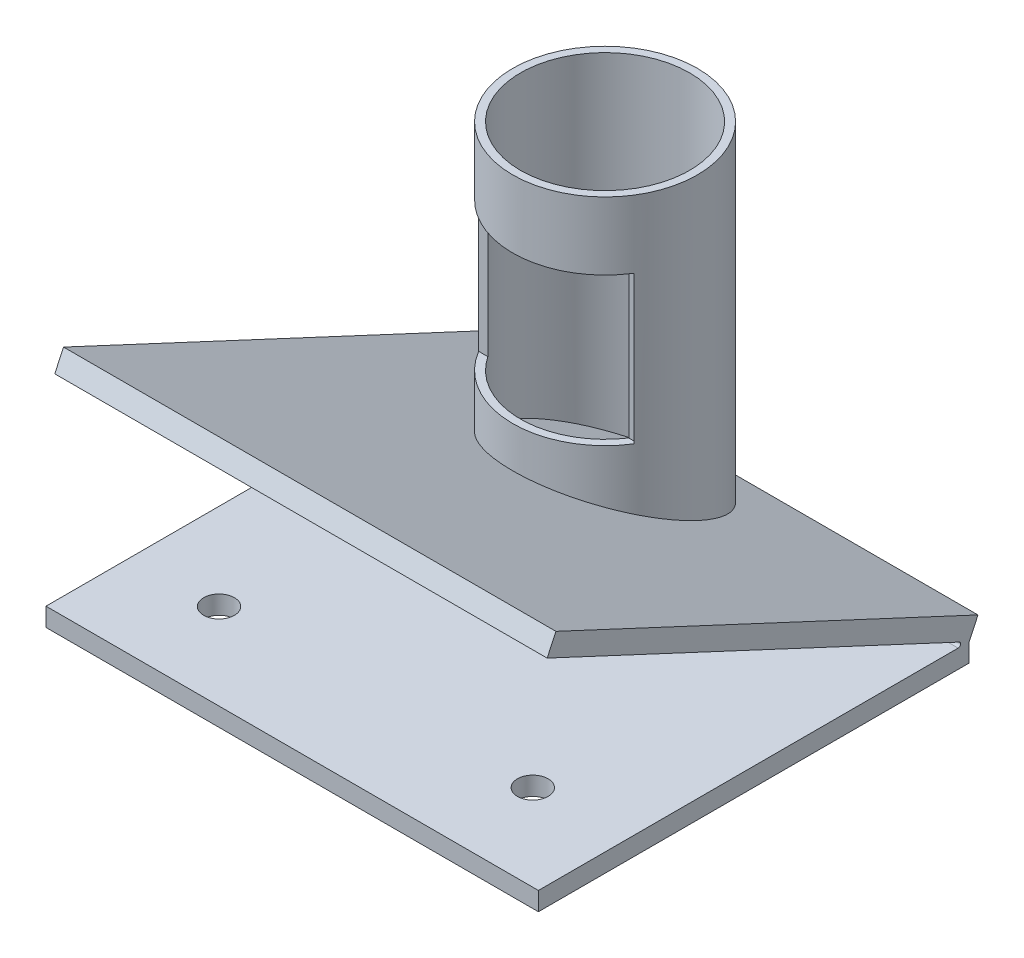
SolidWorks part; units mm, degrees
ref_plane "Front Plane" through (0, 0, 0) normal (0, 0, 1) x (1, 0, 0)
ref_plane "Top Plane" through (0, 0, 0) normal (0, 1, 0) x (1, 0, 0)
ref_plane "Right Plane" through (0, 0, 0) normal (1, 0, 0) x (0, 0, -1)
sketch "Sketch2" plane through (0, 0, 0) normal (1, 0, 0) x (0, 0, -1)
  line L0 (166.8238, 11.3126) -> (-167.8756, 167.3855)
  line L1 (-175, 7.5) -> (165.9786, 7.5)
  line L2 (-175, 7.5) -> (-175, -7.5)
  line L3 (-175, -7.5) -> (175, -7.5)
  line L4 (175, 7.5) -> (175, -7.5)
  line L5 (-175, 7.5) -> (175, -7.5) construction
  line L6 (-175, -7.5) -> (175, 7.5) construction
  line L7 (175, 7.5) -> (182.1244, 22.7784)
  line L8 (-167.8756, 167.3855) -> (-160.7511, 182.6639)
  line L9 (182.1244, 22.7784) -> (-160.7511, 182.6639)
  arc A0 (165.9786, 7.5) -> (166.8238, 11.3126) centre (165.9786, 9.5) ccw
  point P0 (0, 0)
  dimension "D5" = 2
  dimension "D1" = 350
  dimension "D2" = 15
  dimension "D3" = 350
  dimension "D4" = 25
extrude "Boss-Extrude1" add sketch "Sketch2" against normal blind 400
sketch "Sketch3" plane through (0, -7.5, 0) normal (0, -1, 0) x (1, 0, 0)
  circle A0 centre (-200, 0) radius 30
extrude "Cut-Extrude1" cut sketch "Sketch3" against normal blind 5
sketch "Sketch4" plane through (0, -7.5, 0) normal (0, -1, 0) x (1, 0, 0)
  circle A0 centre (-329.4776, 104.9328) radius 12.4624
  circle A1 centre (-74.6166, 104.9328) radius 12.4624
  point P4 (-74.6166, 104.9328)
extrude "Cut-Extrude2" cut sketch "Sketch4" against normal blind 25
sketch "Sketch5" plane through (0, 7.5, 0) normal (0, 1, 0) x (1, 0, 0)
  line L0 (0, 167.9786) -> (-400, 167.9786) construction
  circle A0 centre (-213.8178, 92.9786) radius 75
  circle A1 centre (-213.8178, 92.9786) radius 68.6899
  dimension "D2" = 150
  dimension "D1" = 75
extrude "Boss-Extrude3" add sketch "Sketch5" along normal blind 300 separate body
sketch "Sketch6" plane through (-400, 0, 0) normal (-1, 0, 0) x (0, 0, 1)
  line L0 (0.5259, 89.3491) -> (-166.8238, 11.3126)
  line L1 (167.8756, 167.3855) -> (-166.8238, 11.3126) construction
  line L3 (-165.9786, 7.5) -> (175, 7.5) construction
  line L4 (-165.9786, 7.5) -> (-3.0664, 7.5)
  line L5 (-3.0664, 7.5) -> (0.5259, 89.3491)
  arc A0 (-166.8238, 11.3126) -> (-165.9786, 7.5) centre (-165.9786, 9.5) ccw construction
  arc A1 (-166.8238, 11.3126) -> (-165.9786, 7.5) centre (-165.9786, 9.5) ccw
extrude "Cut-Extrude3" cut sketch "Sketch6" against normal blind 500
ref_plane "Plane1" through (0, 0, -5) normal (0, 0, 1) x (1, 0, 0)
sketch "Sketch8" plane through (0, 0, -5) normal (0, 0, 1) x (1, 0, 0)
  line L1 (-280.377, 252.5305) -> (-150.377, 252.5305)
  line L2 (-280.377, 252.5305) -> (-280.377, 132.5305)
  line L3 (-280.377, 132.5305) -> (-150.377, 132.5305)
  line L4 (-150.377, 252.5305) -> (-150.377, 132.5305)
  line L5 (-280.377, 252.5305) -> (-150.377, 132.5305) construction
  line L6 (-280.377, 132.5305) -> (-150.377, 252.5305) construction
  point P0 (-215.377, 192.5305)
  dimension "D1" = 120
  dimension "D2" = 130
extrude "Cut-Extrude4" cut sketch "Sketch8" against normal blind 50
